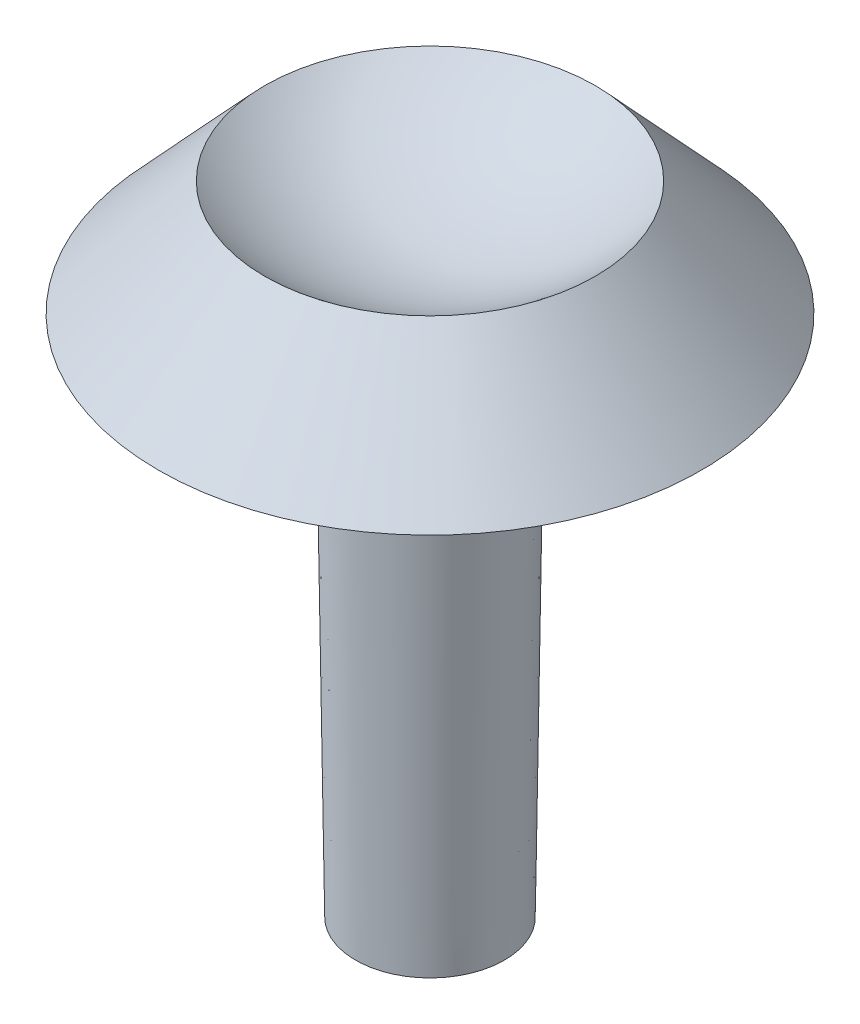
SolidWorks part; units mm, degrees
ref_plane "Front Plane" through (0, 0, 0) normal (0, 0, 1) x (1, 0, 0)
ref_plane "Top Plane" through (0, 0, 0) normal (0, 1, 0) x (1, 0, 0)
ref_plane "Right Plane" through (0, 0, 0) normal (1, 0, 0) x (0, 0, -1)
sketch "Sketch1" plane through (0, 0, 0) normal (0, 0, 1) x (1, 0, 0)
  line L0 (0, -41.1) -> (0, -3.9) construction
  line L1 (0, -41.1) -> (2.9, -41.1)
  line L2 (2.9, -41.1) -> (2.9, -27.1)
  line L3 (2.9, -27.1) -> (0, -27.1)
  line L4 (0, -27.1) -> (0, -3.9)
  line L5 (2.9, -41.1) -> (4.8, -41.1)
  line L8 (0, -7.4) -> (17.5, -7.4)
  line L9 (5.25, -3.0425) -> (5.25, -7.4)
  line L10 (4.8, -41.1) -> (5.25, -7.4)
  line L12 (10.6532, 0) -> (17.5, -7.4)
  line L13 (0, 12.6) -> (0, 0)
  line L14 (14.7752, -7.4) -> (9.041, -1.2025)
  line L15 (10.6532, 0) -> (37.7926, 0) construction
  arc A0 (0, -3.9) -> (10.6532, 0) centre (0, 12.6) ccw
  spline S0 degree 2 poles (0, -5.9) (7.1889, -5.9) (11.9965, -1.4518) knots 0 0 0 1 1 1
  point P19 (0, 0)
  point P21 (0, 0)
  dimension "D7" = 33
  dimension "D8" = 20
  dimension "D12" = 2
  dimension "D1" = 41.1
  dimension "D2" = 2.9
  dimension "D3" = 14
  dimension "D4" = 1.9
  dimension "D9" = 17.5
  dimension "D10" = 47.224
  dimension "D11" = 2
revolve "Revolve2" add sketch "Sketch1" angle 360 about L4
sketch "Sketch3" plane through (0, 0, 0) normal (1, 0, 0) x (0, 0, -1)
  line L0 (-5.25, -5.2221) -> (-12.7601, -5.2221)
  line L1 (5.25, -5.2221) -> (-5.25, -5.2221) construction
  line L2 (-10.4488, -2.724) -> (-14.7752, -7.4) construction
  line L3 (-12.7601, -5.2221) -> (-10.4488, -2.724)
  line L4 (10.4488, -2.724) -> (-10.4488, -2.724) construction
  spline S0 degree 3 poles (-10.4488, -2.724) (-10.4363, -2.733) (-10.3946, -2.7633) (-10.3232, -2.8144) (-9.9364, -3.0878) (-9.3843, -3.4454) (-8.6231, -3.8777) (-7.9723, -4.2097) (-7.2714, -4.5259) (-6.5333, -4.8172) (-5.9894, -5.0015) (-5.6519, -5.1054) (-5.5447, -5.1376) (-5.4372, -5.1691) (-5.3389, -5.1973) (-5.2764, -5.2147) (-5.2499, -5.2221) knots 0 0 0 0 0.007943 0.02668 0.045402 0.252981 0.366731 0.498173 0.630816 0.764426 0.908532 0.927807 0.947107 0.966433 0.985786 1 1 1 1 construction
  spline S1 degree 3 poles (-10.4488, -2.724) (-8.8149, -3.8797) (-7.0898, -4.664) (-5.25, -5.2221) knots 0 0 0 0 1 1 1 1
extrude "Boss-Extrude4" add sketch "Sketch3" along normal mid plane 1 separate body
